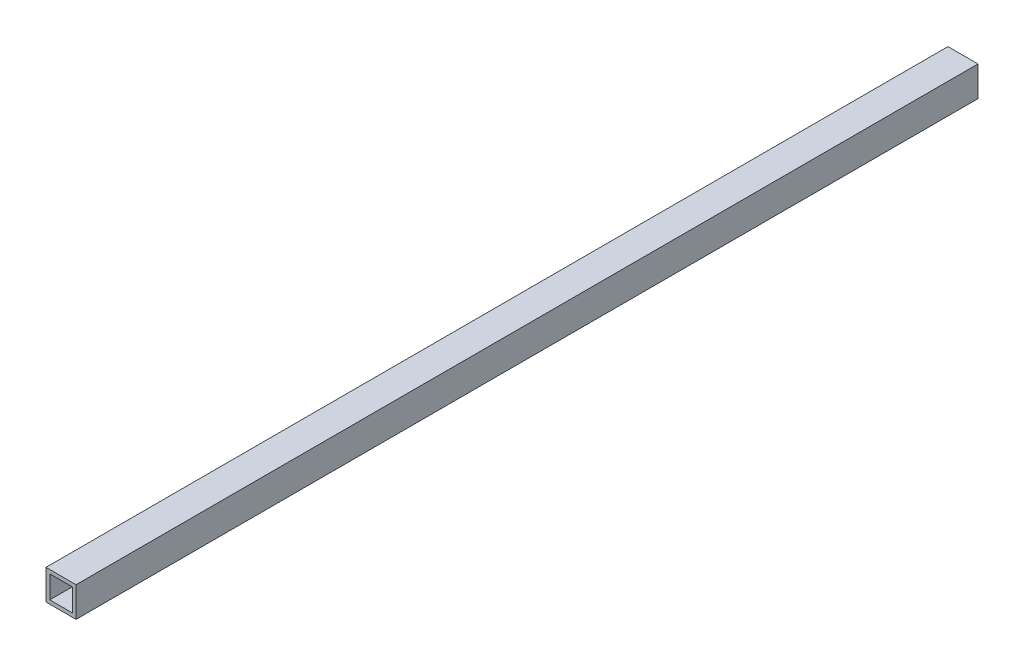
SolidWorks part; units mm, degrees
material "6061 Alloy"
ref_plane "Front Plane" through (0, 0, 0) normal (0, 0, 1) x (1, 0, 0)
ref_plane "Top Plane" through (0, 0, 0) normal (0, 1, 0) x (1, 0, 0)
ref_plane "Right Plane" through (0, 0, 0) normal (1, 0, 0) x (0, 0, -1)
sketch "Sketch1" plane through (0, 0, 0) normal (0, 0, 1) x (1, 0, 0)
  line L0 (12.7, 0) -> (9.525, 0) construction
  line L1 (-12.7, 0) -> (12.7, 0) construction
  line L2 (0, 12.7) -> (0, -12.7)
  point P7 (0, 0)
sketch "Sketch2" plane through (0, 0, 0) normal (1, 0, 0) x (0, 0, -1)
  line L0 (381, 0) -> (-381, 0)
  point P4 (0, 0)
  dimension "Length" = 762
sketch "Sketch3" plane through (0, 0, 0) normal (0, 0, 1) x (1, 0, 0)
  line L0 (-12.7, 0) -> (12.7, 0) construction
  line L5 (12.7, -12.7) -> (-12.7, -12.7)
  line L6 (12.7, -12.7) -> (12.7, 12.7)
  line L11 (12.7, 12.7) -> (-12.7, 12.7)
  line L12 (-12.7, -12.7) -> (-12.7, 12.7)
  line L14 (12.7, -12.7) -> (-12.7, 12.7) construction
  line L15 (12.7, 12.7) -> (-12.7, -12.7) construction
  line L16 (9.525, -9.525) -> (-9.525, -9.525)
  line L17 (9.525, -9.525) -> (9.525, 9.525)
  line L18 (9.525, 9.525) -> (-9.525, 9.525)
  line L19 (-9.525, -9.525) -> (-9.525, 9.525)
  line L20 (9.525, -9.525) -> (-9.525, 9.525) construction
  line L21 (9.525, 9.525) -> (-9.525, -9.525) construction
  point P0 (0, 0)
  point P5 (0, 0)
  point P13 (9.525, -12.7)
  dimension "D1" = 3.175
  dimension "D3" = 25.4
  dimension "D4" = 25.4
extrude "Boss-Extrude1" add sketch "Sketch3" along normal up to vertex (381 mm away) and the other way up to vertex (381 mm away) up to point (0, 0, 381) other way up to point (0, 0, -381)
sketch "Sketch5" plane through (0, 0, 0) normal (1, 0, 0) x (0, 0, -1)
  line L0 (-381, 0) -> (381, 0) construction
  line L3 (-381, -12.7) -> (-381, 12.7) construction
  line L4 (381, -12.7) -> (381, 12.7) construction
  point P6 (-352.425, 0)
  point P7 (-342.9, 0)
  point P8 (342.9, 0)
  point P10 (352.425, 0)
  dimension "D1" = 28.575
  dimension "D2" = 38.1
  dimension "D3" = 28.575
  dimension "D4" = 38.1
equation "\"D1@Sketch3\"=\"Wall thickness@Sketch1\""
equation "\"D1@Sketch5\"=\"Width@Sketch1\"*1.125"
equation "\"D2@Sketch5\"=\"Width@Sketch1\"*1.5"
equation "\"D3@Sketch5\"=\"D1@Sketch5\""
equation "\"D4@Sketch5\"=\"D2@Sketch5\""
equation "\"D2@Sketch3\"=\"Wall Thickness@Sketch1\""
